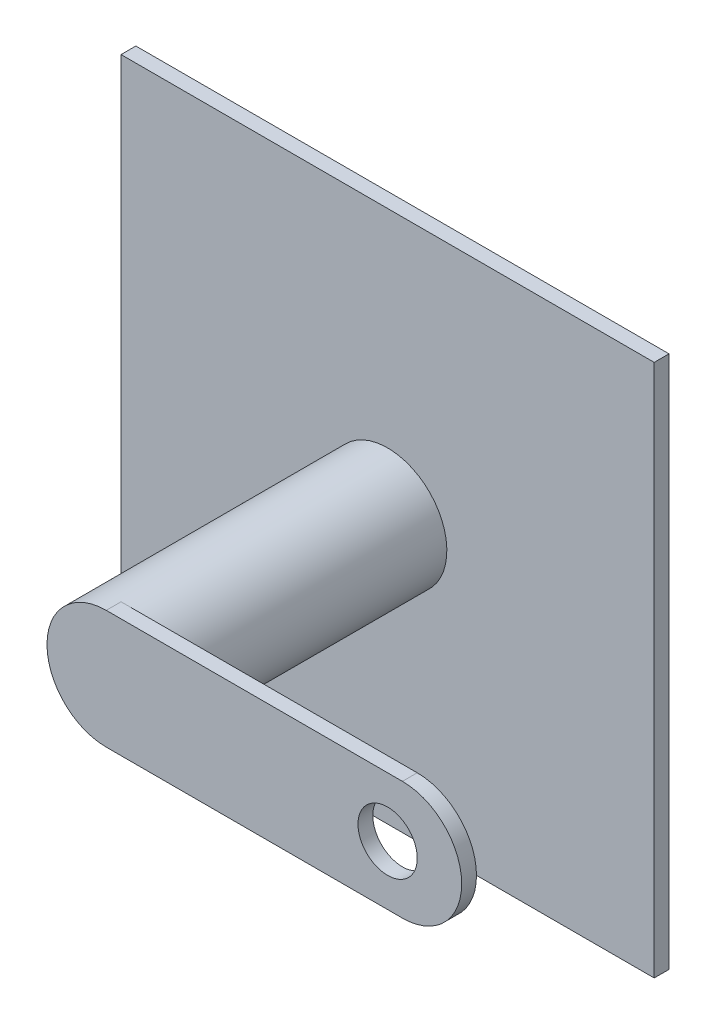
SolidWorks part; units mm, degrees
ref_plane "Front Plane" through (0, 0, 0) normal (0, 0, 1) x (1, 0, 0)
ref_plane "Top Plane" through (0, 0, 0) normal (0, 1, 0) x (1, 0, 0)
ref_plane "Right Plane" through (0, 0, 0) normal (1, 0, 0) x (0, 0, -1)
sketch "Sketch1" plane through (0, 0, 0) normal (0, 1, 0) x (1, 0, 0)
  line L0 (-90, 0) -> (90, 0) construction
  line L1 (-90, 90) -> (90, 90)
  line L2 (-90, 90) -> (-90, -90)
  line L3 (-90, -90) -> (90, -90)
  line L4 (90, 90) -> (90, -90)
  line L5 (-90, 90) -> (90, -90) construction
  line L6 (-90, -90) -> (90, 90) construction
  line L7 (0, 0) -> (0, -90) construction
  point P0 (0, 0)
  dimension "D1" = 180
  dimension "D2" = 180
extrude "Boss-Extrude1" add sketch "Sketch1" along normal blind 5 contours L2 L1 L4 L3
sketch "Sketch2" plane through (0, 5, 0) normal (0, 1, 0) x (1, 0, 0)
  line L0 (-90, 0) -> (90, 0) construction
  line L1 (-90, 90) -> (-90, -90) construction
  line L2 (90, 90) -> (90, -90) construction
  line L3 (0, 0) -> (0, -90) construction
  line L4 (-90, -90) -> (90, -90) construction
  line L5 (0, 0) -> (-90, -90) construction
  circle A0 centre (0, 0) radius 20
  dimension "D3" = 40
  dimension "D1" = 90
extrude "Boss-Extrude2" add sketch "Sketch2" along normal blind 95
sketch "Sketch3" plane through (0, 100, 0) normal (0, 1, 0) x (1, 0, 0)
  line L0 (0, 20) -> (100, 20)
  line L2 (100, -20) -> (0, -20)
  arc A1 (100, -20) -> (100, 20) centre (100, 0) ccw
  circle A2 centre (0, 0) radius 20
  arc A3 (0, 20) -> (0, -20) centre (0, 0) ccw
  dimension "D1" = 0
  dimension "D2" = 2
extrude "Boss-Extrude3" add sketch "Sketch3" against normal blind 5 contours A3 L2 A1 L0
sketch "Sketch4" plane through (0, 100, 0) normal (0, 1, 0) x (1, 0, 0)
  line L0 (95, 0) -> (120, 0) construction
  arc A0 (100, -20) -> (100, 20) centre (100, 0) ccw construction
  circle A1 centre (95, 0) radius 10
  dimension "D2" = 20
  dimension "D1" = 25
extrude "Cut-Extrude1" cut sketch "Sketch4" against normal up to next contours A1
sketch "Sketch5" plane through (0, 0, 0) normal (0, -1, 0) x (1, 0, 0)
  point P0 (0, 0)
move or copy body "Body-Move/Copy1" bodies to move or copy 105 copy no rotation origin (0, 0, 0) rotation axis (1, 0, 0) rotation angle 90
